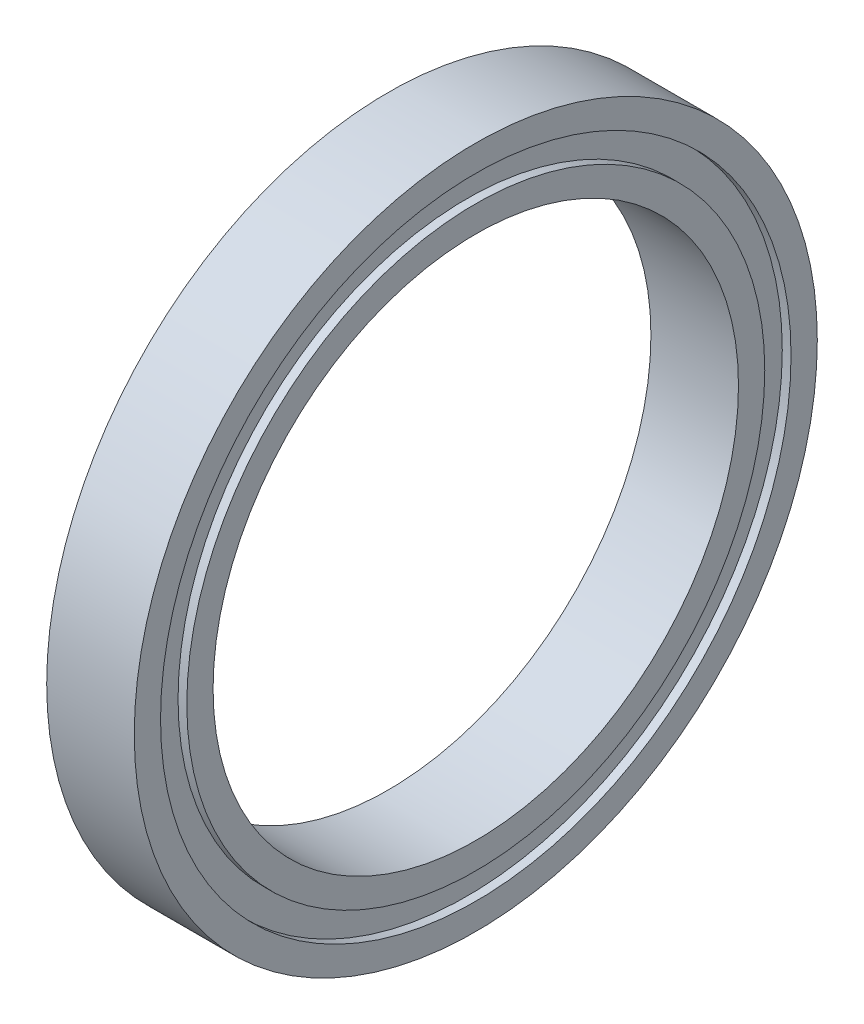
SolidWorks part; units mm, degrees
material "1023 碳钢板 (SS)"
ref_plane "前视基准面" through (0, 0, 0) normal (0, 0, 1) x (1, 0, 0)
ref_plane "上视基准面" through (0, 0, 0) normal (0, 1, 0) x (1, 0, 0)
ref_plane "右视基准面" through (0, 0, 0) normal (1, 0, 0) x (0, 0, -1)
other "Configuration Table"
sketch "草图1" plane through (0, 0, 0) normal (1, 0, 0) x (0, 0, -1)
  circle A0 centre (0, 0) radius 30
  circle A1 centre (0, 0) radius 39
  dimension "D1" = 60
  dimension "D2" = 78
extrude "凸台-拉伸1" add sketch "草图1" along normal blind 10
sketch "草图2" plane through (10, 0, 0) normal (1, 0, 0) x (0, 0, -1)
  circle A0 centre (0, 0) radius 33
  circle A1 centre (0, 0) radius 36
  circle A2 centre (0, 0) radius 30 construction
  circle A3 centre (0, 0) radius 39 construction
  dimension "D1" = 3
  dimension "D2" = 3
extrude "切除-拉伸1" cut sketch "草图2" against normal blind 1
sketch "草图3" plane through (0, 0, 0) normal (-1, 0, 0) x (0, 0, 1)
  circle A1 centre (0, 0) radius 36
  circle A2 centre (0, 0) radius 36
  circle A3 centre (0, 0) radius 33
  circle A4 centre (0, 0) radius 33
  dimension "D1" = 0
  dimension "D2" = 0
extrude "切除-拉伸2" cut sketch "草图3" against normal blind 1
